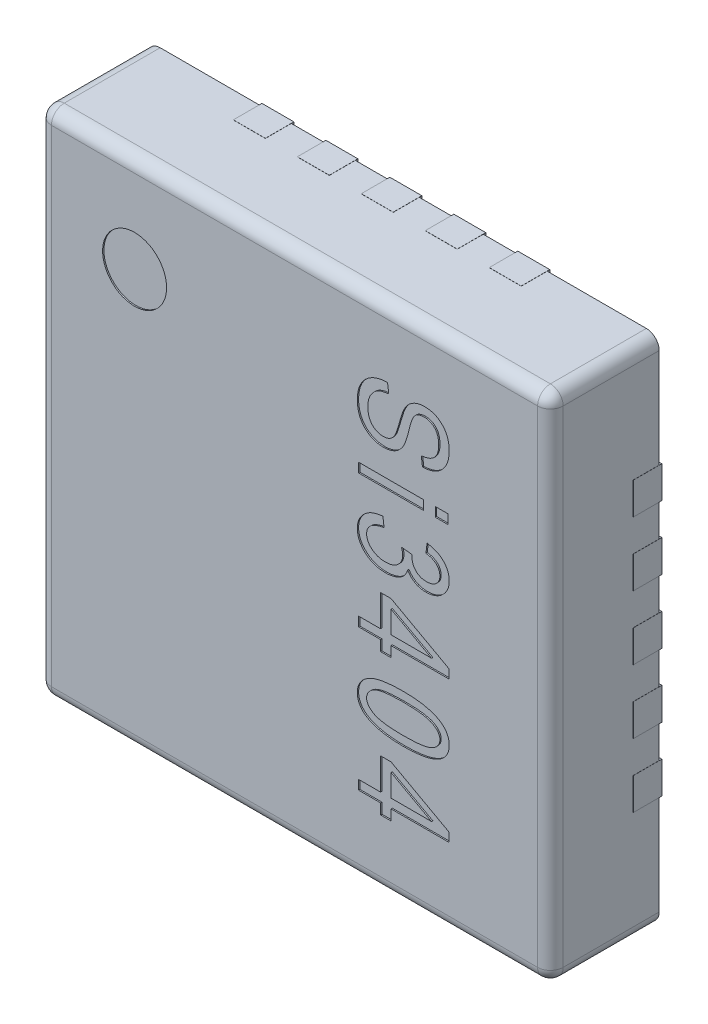
SolidWorks part; units mm, degrees
ref_plane "Front Plane" through (0, 0, 0) normal (0, 0, 1) x (1, 0, 0)
ref_plane "Top Plane" through (0, 0, 0) normal (0, 1, 0) x (1, 0, 0)
ref_plane "Right Plane" through (0, 0, 0) normal (1, 0, 0) x (0, 0, -1)
sketch "Sketch1" plane through (0, 0, 0) normal (0, 0, 1) x (1, 0, 0)
  line L5 (2, -2) -> (-2, -2)
  line L6 (2, -2) -> (2, 2)
  line L7 (2, 2) -> (-2, 2)
  line L8 (-2, -2) -> (-2, 2)
  line L9 (2, -2) -> (-2, 2) construction
  line L10 (2, 2) -> (-2, -2) construction
  point P0 (0, 0)
  dimension "D1" = 4
extrude "Boss-Extrude1" add sketch "Sketch1" along normal blind 0.85
fillet "Fillet1" radius 0.1 8 edges at (-2, -2, 0.425) (-2, 0, 0.85) (0, -2, 0.85) (2, -2, 0.425) (2, 0, 0.85) (0, 2, 0.85) (-2, 2, 0.425) (2, 2, 0.425)
sketch "Sketch2" plane through (0, 0, 0) normal (0, 0, -1) x (-1, 0, 0)
  line L0 (1.2634, 1.0366) -> (1.0366, 1.2634)
  line L1 (0.9482, 1.3) -> (-1.175, 1.3)
  line L2 (1.3, 0.9482) -> (1.3, -1.175)
  line L3 (1.175, -1.3) -> (-1.175, -1.3)
  line L4 (-1.3, 1.175) -> (-1.3, -1.175)
  line L5 (1.3, 1.3) -> (-1.3, -1.3) construction
  line L6 (1.3, -1.3) -> (-1.3, 1.3) construction
  line L7 (-1.9, 2) -> (1.9, 2) construction
  line L8 (-0.125, 2.001) -> (0.125, 2.001)
  line L9 (-0.125, 2.001) -> (-0.125, 1.726)
  line L10 (0, 1.601) -> (0.125, 1.601) construction
  line L11 (0.125, 2.001) -> (0.125, 1.726)
  line L12 (-0.125, 2.001) -> (0.0965, 1.6466) construction
  line L13 (-0.0965, 1.6466) -> (0.125, 2.001) construction
  line L14 (-0.125, 1.601) -> (0, 1.601) construction
  line L15 (-0.125, 1.601) -> (-0.0965, 1.6466) construction
  line L16 (-0.125, 1.726) -> (-0.125, 1.601) construction
  line L17 (0.0965, 1.6466) -> (0.125, 1.601) construction
  line L18 (0.125, 1.726) -> (0.125, 1.601) construction
  line L19 (-0.375, 2.001) -> (-0.375, 1.726)
  line L20 (-0.625, 2.001) -> (-0.625, 1.726)
  line L21 (-0.625, 2.001) -> (-0.375, 2.001)
  line L22 (-0.875, 2.001) -> (-0.875, 1.726)
  line L23 (-1.125, 2.001) -> (-1.125, 1.726)
  line L24 (-1.125, 2.001) -> (-0.875, 2.001)
  line L25 (0, -1000) -> (0, 49000) construction
  line L26 (-1000, 0) -> (49000, 0) construction
  line L27 (1.125, 2.001) -> (0.875, 2.001)
  line L28 (1.125, 2.001) -> (1.125, 1.726)
  line L29 (0.875, 2.001) -> (0.875, 1.726)
  line L30 (0.625, 2.001) -> (0.375, 2.001)
  line L31 (0.625, 2.001) -> (0.625, 1.726)
  line L32 (0.375, 2.001) -> (0.375, 1.726)
  line L33 (1.125, -2.001) -> (1.125, -1.726)
  line L34 (0.875, -2.001) -> (0.875, -1.726)
  line L35 (1.125, -2.001) -> (0.875, -2.001)
  line L36 (0.625, -2.001) -> (0.625, -1.726)
  line L37 (0.375, -2.001) -> (0.375, -1.726)
  line L38 (0.625, -2.001) -> (0.375, -2.001)
  line L39 (-0.125, -2.001) -> (0.125, -2.001)
  line L40 (-0.125, -2.001) -> (-0.125, -1.726)
  line L41 (0.125, -2.001) -> (0.125, -1.726)
  line L42 (-0.625, -2.001) -> (-0.375, -2.001)
  line L43 (-0.625, -2.001) -> (-0.625, -1.726)
  line L44 (-0.375, -2.001) -> (-0.375, -1.726)
  line L45 (-1.125, -2.001) -> (-0.875, -2.001)
  line L46 (-1.125, -2.001) -> (-1.125, -1.726)
  line L47 (-0.875, -2.001) -> (-0.875, -1.726)
  line L48 (2.001, -1.125) -> (2.001, -0.875)
  line L49 (2.001, -0.875) -> (1.726, -0.875)
  line L50 (2.001, -1.125) -> (1.726, -1.125)
  line L51 (2.001, -0.625) -> (2.001, -0.375)
  line L52 (2.001, -0.375) -> (1.726, -0.375)
  line L53 (2.001, -0.625) -> (1.726, -0.625)
  line L54 (2.001, 0.125) -> (1.726, 0.125)
  line L55 (2.001, -0.125) -> (1.726, -0.125)
  line L56 (2.001, 0.125) -> (2.001, -0.125)
  line L57 (2.001, 0.625) -> (1.726, 0.625)
  line L58 (2.001, 0.375) -> (1.726, 0.375)
  line L59 (2.001, 0.625) -> (2.001, 0.375)
  line L60 (2.001, 1.125) -> (1.726, 1.125)
  line L61 (2.001, 0.875) -> (1.726, 0.875)
  line L62 (2.001, 1.125) -> (2.001, 0.875)
  line L63 (-2.001, -1.125) -> (-1.726, -1.125)
  line L64 (-2.001, -0.875) -> (-1.726, -0.875)
  line L65 (-2.001, -1.125) -> (-2.001, -0.875)
  line L66 (-2.001, -0.625) -> (-1.726, -0.625)
  line L67 (-2.001, -0.375) -> (-1.726, -0.375)
  line L68 (-2.001, -0.625) -> (-2.001, -0.375)
  line L69 (-2.001, 0.125) -> (-2.001, -0.125)
  line L70 (-2.001, 0.125) -> (-1.726, 0.125)
  line L71 (-2.001, -0.125) -> (-1.726, -0.125)
  line L72 (-2.001, 0.625) -> (-2.001, 0.375)
  line L73 (-2.001, 0.625) -> (-1.726, 0.625)
  line L74 (-2.001, 0.375) -> (-1.726, 0.375)
  line L75 (-2.001, 1.125) -> (-2.001, 0.875)
  line L76 (-2.001, 1.125) -> (-1.726, 1.125)
  line L77 (-2.001, 0.875) -> (-1.726, 0.875)
  arc A0 (-0.125, 1.726) -> (0.125, 1.726) centre (0, 1.726) ccw
  arc A1 (-0.625, 1.726) -> (-0.375, 1.726) centre (-0.5, 1.726) ccw
  arc A2 (-1.125, 1.726) -> (-0.875, 1.726) centre (-1, 1.726) ccw
  arc A3 (1.125, 1.726) -> (0.875, 1.726) centre (1, 1.726) cw
  arc A4 (0.625, 1.726) -> (0.375, 1.726) centre (0.5, 1.726) cw
  arc A5 (1.125, -1.726) -> (0.875, -1.726) centre (1, -1.726) ccw
  arc A6 (0.625, -1.726) -> (0.375, -1.726) centre (0.5, -1.726) ccw
  arc A7 (-0.125, -1.726) -> (0.125, -1.726) centre (0, -1.726) cw
  arc A8 (-0.625, -1.726) -> (-0.375, -1.726) centre (-0.5, -1.726) cw
  arc A9 (-1.125, -1.726) -> (-0.875, -1.726) centre (-1, -1.726) cw
  arc A10 (1.726, -1.125) -> (1.726, -0.875) centre (1.726, -1) cw
  arc A11 (1.726, -0.625) -> (1.726, -0.375) centre (1.726, -0.5) cw
  arc A12 (1.726, 0.125) -> (1.726, -0.125) centre (1.726, 0) ccw
  arc A13 (1.726, 0.625) -> (1.726, 0.375) centre (1.726, 0.5) ccw
  arc A14 (1.726, 1.125) -> (1.726, 0.875) centre (1.726, 1) ccw
  arc A15 (-1.726, -1.125) -> (-1.726, -0.875) centre (-1.726, -1) ccw
  arc A16 (-1.726, -0.625) -> (-1.726, -0.375) centre (-1.726, -0.5) ccw
  arc A17 (-1.726, 0.125) -> (-1.726, -0.125) centre (-1.726, 0) cw
  arc A18 (-1.726, 0.625) -> (-1.726, 0.375) centre (-1.726, 0.5) cw
  arc A19 (-1.726, 1.125) -> (-1.726, 0.875) centre (-1.726, 1) cw
  arc A20 (1.3, -1.175) -> (1.175, -1.3) centre (1.175, -1.175) cw
  arc A21 (-1.175, -1.3) -> (-1.3, -1.175) centre (-1.175, -1.175) cw
  arc A22 (1.2634, 1.0366) -> (1.3, 0.9482) centre (1.175, 0.9482) cw
  arc A23 (1.0366, 1.2634) -> (0.9482, 1.3) centre (0.9482, 1.175) ccw
  arc A24 (-1.175, 1.3) -> (-1.3, 1.175) centre (-1.175, 1.175) ccw
  point P0 (0, 0)
  point P8 (0, 1.801)
  point P130 (1, 1.3)
  dimension "D8" = 3
  dimension "D10" = 0.125
  dimension "D11" = 0.125
  dimension "D12" = 0.125
  dimension "D13" = 0.125
  dimension "D14" = 0.125
  dimension "D1" = 2.6
  dimension "D2" = 0.3
  dimension "D3" = 45
  dimension "D4" = 2.6
  dimension "D5" = 0.001
  dimension "D6" = 0.4
  dimension "D7" = 0.25
  dimension "D9" = 0.5
extrude "Boss-Extrude2" add sketch "Sketch2" along normal blind 0.02 and the other way blind 0.203 separate body
sketch "Sketch3" plane through (0, 0, 0.85) normal (0, 0, 1) x (1, 0, 0)
  line L0 (2, 2) -> (-2, 2) construction
  line L1 (-2, 2) -> (-2, -2) construction
  line L2 (0.5, 2) -> (0.5, -2) construction
  line L3 (1.9, -2) -> (-1.9, -2) construction
  line L4 (2, 1.9) -> (2, -1.9) construction
  line L5 (-1.9, 2) -> (1.9, 2) construction
  circle A0 centre (-1.25, 1.25) radius 0.25
  text T0 "Si3404" font "Arial Narrow" height 0.7
  point P12 (1.25, 2)
  dimension "D1" = 0.5
  dimension "D2" = 0.75
  dimension "D3" = 0.75
  dimension "D4" = 1.5
extrude "Cut-Extrude1" cut sketch "Sketch3" against normal blind 0.01
